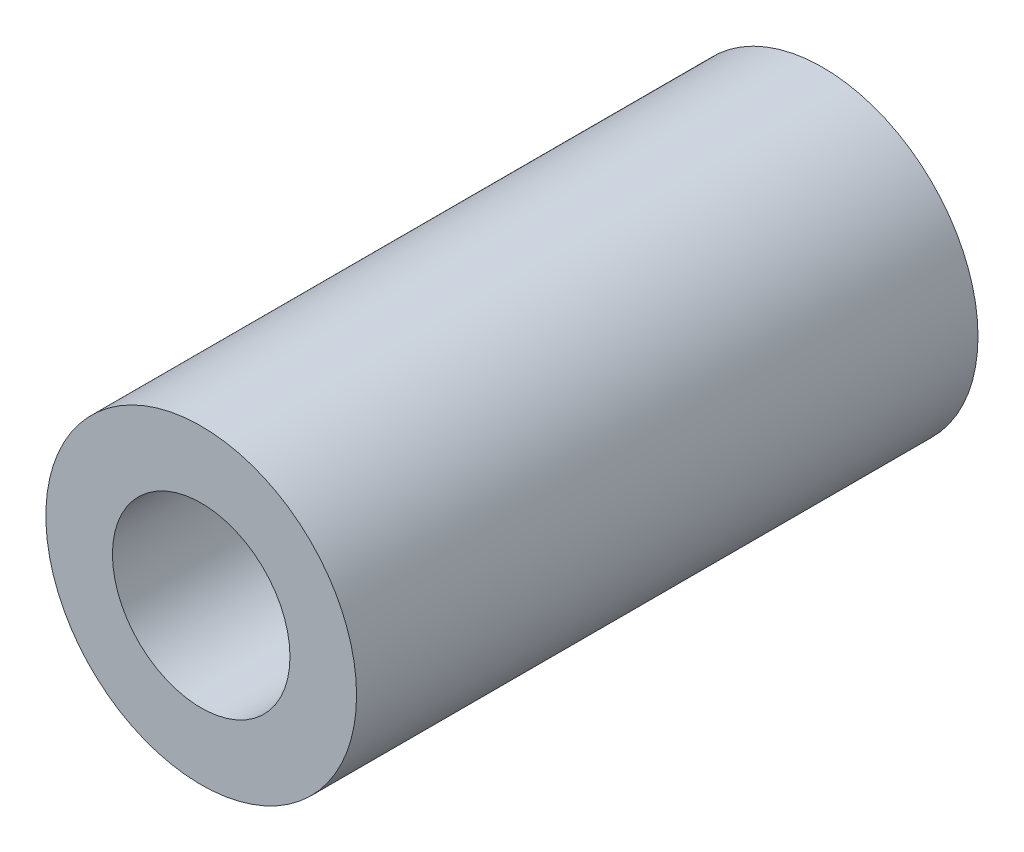
SolidWorks part; units mm, degrees
material "Nylon 101"
ref_plane "Front Plane" through (0, 0, 0) normal (0, 0, 1) x (1, 0, 0)
ref_plane "Top Plane" through (0, 0, 0) normal (0, 1, 0) x (1, 0, 0)
ref_plane "Right Plane" through (0, 0, 0) normal (1, 0, 0) x (0, 0, -1)
sketch "Sketch1" plane through (0, 0, 0) normal (0, 0, 1) x (1, 0, 0)
  circle A0 centre (0, 0) radius 2
  circle A1 centre (0, 0) radius 3.5
  dimension "D1" = 7
  dimension "D2" = 4
extrude "Boss-Extrude1" add sketch "Sketch1" along normal blind 14
